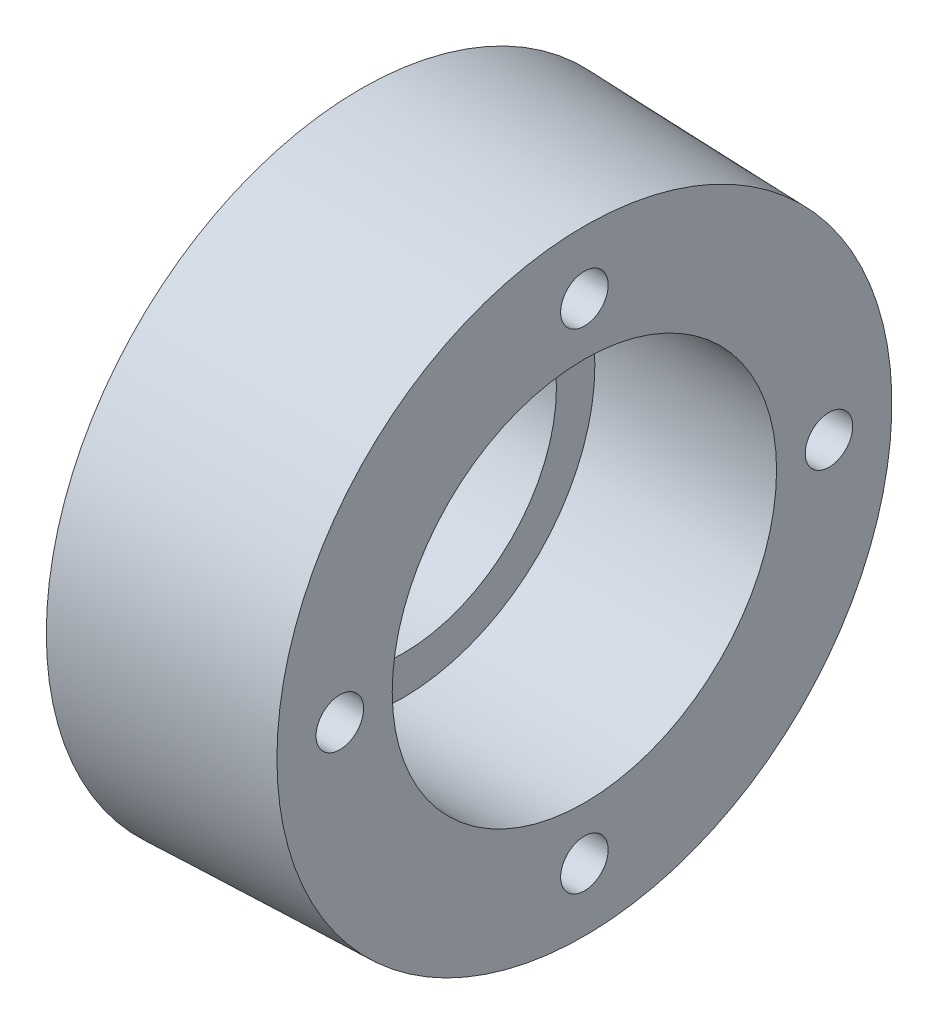
SolidWorks part; units mm, degrees
ref_plane "Ön Düzlem" through (0, 0, 0) normal (0, 0, 1) x (1, 0, 0)
ref_plane "Üst Düzlem" through (0, 0, 0) normal (0, 1, 0) x (1, 0, 0)
ref_plane "Sağ Düzlem" through (0, 0, 0) normal (1, 0, 0) x (0, 0, -1)
sketch "Çizim2" plane through (0, 0, 0) normal (0, 0, 1) x (1, 0, 0)
  line L0 (0, 0) -> (45.7155, 0) construction
  line L1 (0, 22) -> (11, 22)
  line L2 (0, 22) -> (0, 28)
  line L3 (0, 28) -> (5, 28)
  line L4 (5, 28) -> (5, 45)
  line L5 (5, 45) -> (37, 44)
  line L6 (37, 44) -> (37, 27.5)
  line L7 (37, 27.5) -> (11, 27.5)
  line L8 (11, 27.5) -> (11, 22)
  dimension "D1" = 55
  dimension "D2" = 5
  dimension "D3" = 56
  dimension "D4" = 44
  dimension "D5" = 90
  dimension "D6" = 88
  dimension "D7" = 37
  dimension "D8" = 26
revolve "Döndür1" add sketch "Çizim2" angle 360 about L0
hole_wizard "M8 Dişli Delik1" positions "Çizim3" profile "Çizim5" tap size "M8" standard "ISO"
sketch "Çizim3" plane through (37, 0, 0) normal (1, 0, 0) x (0, 0, -1)
  point P0 (0, 35)
  dimension "D1" = 35
sketch "Çizim5" plane through (37, 35, 0) normal (0, 1, 0) x (0, 0, -1)
  line L0 (0, 0) -> (0, 24.2929)
  line L1 (0, 24.2929) -> (3.4, 22.25)
  line L2 (3.4, 22.25) -> (3.4, 0)
  line L5 (3.4, 0) -> (0, 0)
  line L10 (0, 24.2929) -> (-3.4, 22.25) construction
  line L11 (0, -6.35) -> (0, 107.95) construction
  dimension "Tap Drill Dia." = 6.8
  dimension "Tap Drill Depth" = 22.25
  dimension "Drill Angle" = 118
cosmetic thread "Delik Dişi1" parameters "D1"=16, "D2"=8
pattern_circular "Dairesel Kaplama1" count 4 over 360 about axis through (0, 0, 0) along (1, 0, 0) of "M8 Dişli Delik1"
cosmetic thread "Delik Dişi2" parameters "D1"=16, "D2"=8
cosmetic thread "Delik Dişi3" parameters "D1"=16, "D2"=8
cosmetic thread "Delik Dişi4" parameters "D1"=16, "D2"=8
